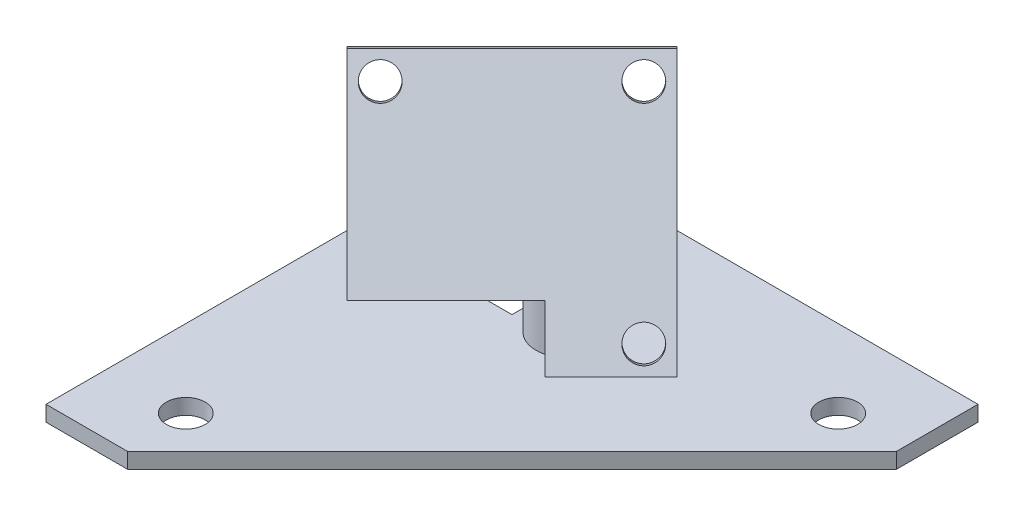
SolidWorks part; units mm, degrees
ref_plane "Front" through (0, 0, 0) normal (0, 0, 1) x (1, 0, 0)
ref_plane "Top" through (0, 0, 0) normal (0, 1, 0) x (1, 0, 0)
ref_plane "Right" through (0, 0, 0) normal (1, 0, 0) x (0, 0, -1)
sketch "草图1" plane through (0, 0, 0) normal (0, 1, 0) x (1, 0, 0)
  line L0 (87.1745, 16.672) -> (1.4976, -69.0049)
  line L1 (0, 0) -> (60, 0)
  line L2 (0, 0) -> (0, -60)
  line L3 (0, -60) -> (60, -60)
  line L4 (60, 0) -> (60, -60)
  line L5 (0, 0) -> (20, 0)
  line L6 (0, 0) -> (0, -20)
  line L7 (0, -20) -> (20, -20)
  line L8 (20, 0) -> (20, -20)
  circle A0 centre (10, -52) radius 2.5
  circle A1 centre (52, -10) radius 2.5
  dimension "D5" = 5
  dimension "D8" = 5
  dimension "D1" = 60
  dimension "D2" = 60
  dimension "D3" = 20
  dimension "D4" = 20
  dimension "D6" = 10
  dimension "D7" = 8
  dimension "D9" = 10
  dimension "D10" = 8
  dimension "D11" = 35
extrude "凸台-拉伸1" add sketch "草图1" along normal blind 2 contours L1 L8 L7 L2 L3 L4
ref_plane "基准面1" through (23.1124, 18.8712, 23.1124) normal (0.6124, 0.5, 0.6124) x (-0.7071, 0, 0.7071)
sketch "草图2" plane through (23.1124, 18.8712, 23.1124) normal (0.6124, 0.5, 0.6124) x (-0.7071, 0, 0.7071)
  line L0 (20.7547, -10.214) -> (-21.3736, -10.214) construction
  line L1 (-15, 16.786) -> (15, 16.786)
  line L2 (-15, 16.786) -> (-15, -13.214)
  line L3 (-15, -13.214) -> (15, -13.214)
  line L4 (15, 16.786) -> (15, -13.214)
  line L5 (-15, 16.786) -> (15, -13.214) construction
  line L6 (-15, -13.214) -> (15, 16.786) construction
  line L7 (0, -2.8326) -> (0, 36.0846) construction
  line L8 (27.4605, 1.786) -> (-33.4746, 1.786) construction
  line L10 (15, 16.786) -> (-3, 16.786)
  line L11 (15, 16.786) -> (15, 9.786)
  line L12 (15, 9.786) -> (-3, 9.786)
  line L13 (-3, 16.786) -> (-3, 9.786)
  circle A0 centre (12, -10.214) radius 2
  circle A1 centre (-12, -10.214) radius 2
  circle A2 centre (-12, 13.786) radius 2
  circle A3 centre (12, 13.786) radius 2
  point P0 (0, 1.786)
  dimension "D4" = 4
  dimension "D1" = 30
  dimension "D2" = 30
  dimension "D3" = 12
  dimension "D5" = 12
  dimension "D6" = 7
  dimension "D7" = 18
extrude "凸台-拉伸3" add sketch "草图2" along normal blind 2 separate body contours L13 L1 L2 L3 L4 L12 A2 A0 A1
sketch "草图4" plane through (0, 2, 0) normal (0, 1, 0) x (1, 0, 0)
  line L12 (28.6936, -38.5931) -> (31.1685, -41.0679)
  line L13 (15.9657, -51.321) -> (28.6936, -38.5931)
  line L14 (-6.3082, -29.0471) -> (15.9657, -51.321)
  line L15 (29.0471, 6.3082) -> (-6.3082, -29.0471)
  line L16 (53.7959, -18.4405) -> (29.0471, 6.3082)
  line L17 (31.1685, -41.0679) -> (53.7959, -18.4405)
  line L18 (28.6936, -38.5931) -> (31.1685, -41.0679)
  line L19 (15.9657, -51.321) -> (28.6936, -38.5931)
  line L20 (-6.3082, -29.0471) -> (15.9657, -51.321)
  line L21 (29.0471, 6.3082) -> (-6.3082, -29.0471)
  line L22 (53.7959, -18.4405) -> (29.0471, 6.3082)
  line L23 (31.1685, -41.0679) -> (53.7959, -18.4405)
  circle A0 centre (25.5116, -18.4405) radius 4
  dimension "D2" = 8
  dimension "D3" = 15
  dimension "D4" = 20
  dimension "D1" = 10
extrude "凸台-拉伸4" add sketch "草图4" along normal up to surface (14.7556 mm away) contours A0
